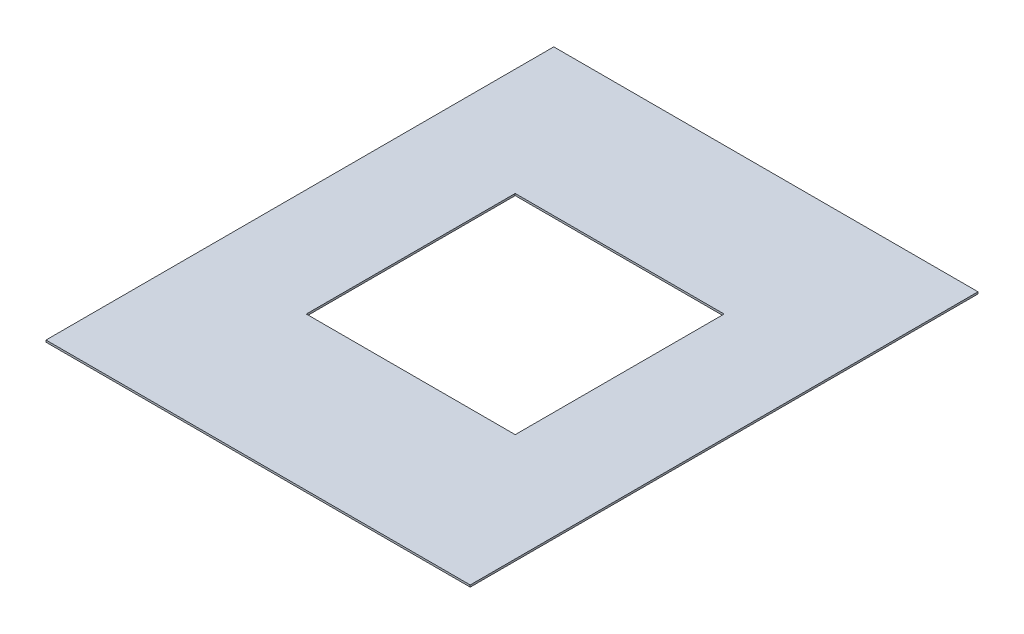
SolidWorks part; units mm, degrees
ref_plane "Front Plane" through (0, 0, 0) normal (0, 0, 1) x (1, 0, 0)
ref_plane "Top Plane" through (0, 0, 0) normal (0, 1, 0) x (1, 0, 0)
ref_plane "Right Plane" through (0, 0, 0) normal (1, 0, 0) x (0, 0, -1)
other "Configuration Table"
sketch "Sketch1" plane through (0, 0, 0) normal (0, 0, 1) x (1, 0, 0)
  line L1 (20, 597) -> (680, 597)
  line L2 (20, 597) -> (20, 600)
  line L3 (20, 600) -> (680, 600)
  line L4 (680, 597) -> (680, 600)
extrude "PACK_kalip_plakasi_3mm_66x79_1" add sketch "Sketch1" against normal blind 790 separate body
sketch "Sketch2" plane through (0, 0, 0) normal (0, 0, 1) x (1, 0, 0)
  line L1 (187.5, 596) -> (512.5, 596)
  line L2 (187.5, 596) -> (187.5, 601)
  line L3 (187.5, 601) -> (512.5, 601)
  line L4 (512.5, 596) -> (512.5, 601)
extrude "PACK_kalip_plakasi_3mm_66x79_2" cut sketch "Sketch2" against normal blind 325 from offset 237.5
